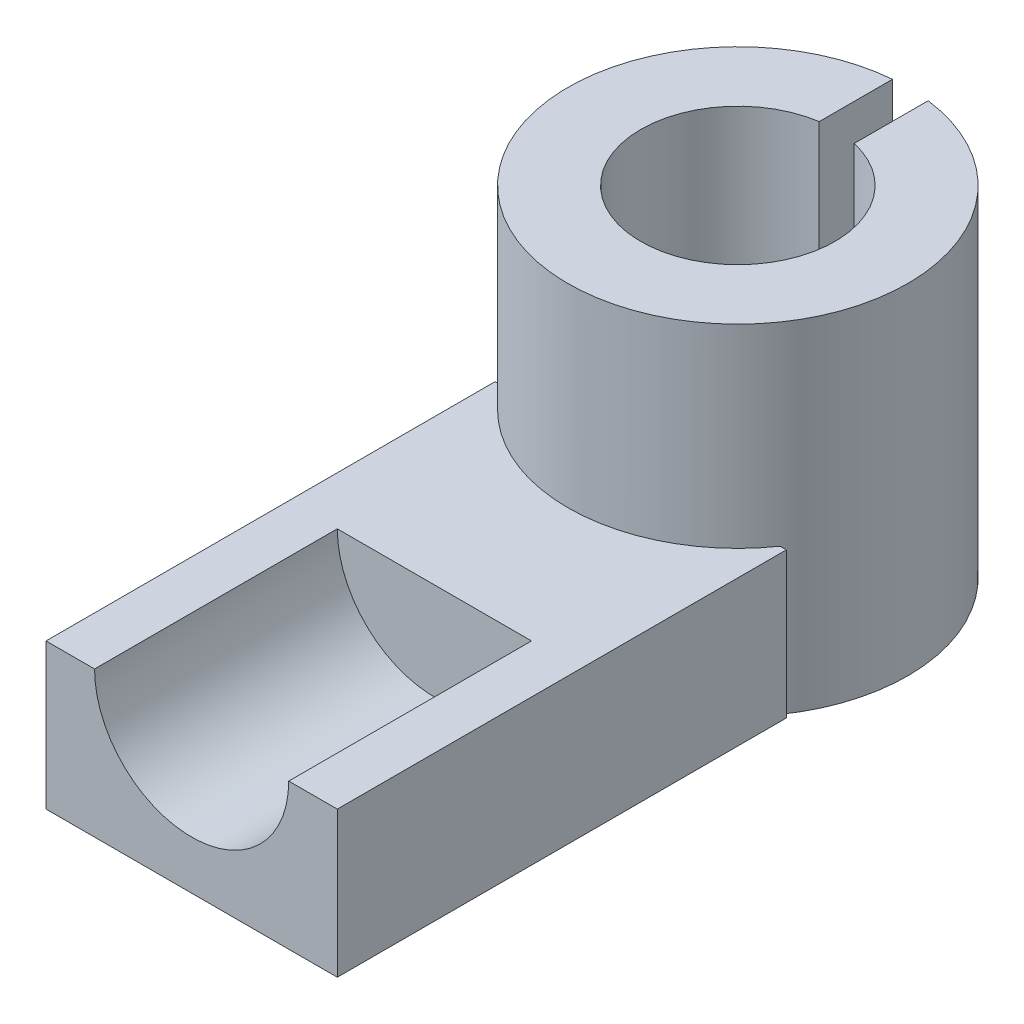
SolidWorks part; units mm, degrees
ref_plane "Front Plane" through (0, 0, 0) normal (0, 0, 1) x (1, 0, 0)
ref_plane "Top Plane" through (0, 0, 0) normal (0, 1, 0) x (1, 0, 0)
ref_plane "Right Plane" through (0, 0, 0) normal (1, 0, 0) x (0, 0, -1)
sketch "Sketch1" plane through (0, 0, 0) normal (0, 1, 0) x (1, 0, 0)
  line L0 (-91.5229, 0) -> (104.9938, 0) construction
  line L1 (0, 66.0669) -> (0, -73.3966) construction
  circle A0 centre (0, 0) radius 16
  circle A1 centre (0, 0) radius 28
  dimension "D1" = 32
  dimension "D2" = 56
extrude "Boss-Extrude1" add sketch "Sketch1" along normal blind 56
sketch "Sketch2" plane through (0, 56, 0) normal (0, 1, 0) x (1, 0, 0)
  line L5 (3.5933, -13.5082) -> (-2.4067, -13.5082)
  line L6 (3.5933, -13.5082) -> (3.5933, 30.9425)
  line L7 (3.5933, 30.9425) -> (-2.4067, 30.9425)
  line L8 (-2.4067, -13.5082) -> (-2.4067, 30.9425)
  line L9 (3.5933, -13.5082) -> (-2.4067, 30.9425) construction
  line L10 (3.5933, 30.9425) -> (-2.4067, -13.5082) construction
  point P0 (0.5933, 8.7171)
  dimension "D1" = 6
extrude "Cut-Extrude1" cut sketch "Sketch2" against normal blind 56
sketch "Sketch3" plane through (0, 0, 0) normal (0, -1, 0) x (1, 0, 0)
  line L0 (0, -28.8727) -> (0, 63.5414) construction
  line L1 (-78.8118, 0) -> (89.5071, 0) construction
  line L3 (-24, 90) -> (24, 90)
  line L4 (-24, 90) -> (-24, 16)
  line L5 (-24, 16) -> (24, 16)
  line L6 (24, 90) -> (24, 16)
  arc A1 (3.5933, -15.5913) -> (-2.4067, -15.818) centre (0, 0) ccw construction
  dimension "D1" = 48
  dimension "D2" = 24
  dimension "D3" = 90
extrude "Boss-Extrude2" add sketch "Sketch3" against normal blind 24
sketch "Sketch4" plane through (0, 0, 90) normal (0, 0, 1) x (1, 0, 0)
  line L0 (24, 24) -> (-24, 24) construction
  line L1 (22.9783, 24) -> (-22.9783, 24) construction
  arc A0 (-16, 24) -> (16, 24) centre (0, 24) ccw
  dimension "D2" = 8
  dimension "D1" = 8
extrude "Cut-Extrude4" cut sketch "Sketch4" against normal blind 40 and the other way through all
